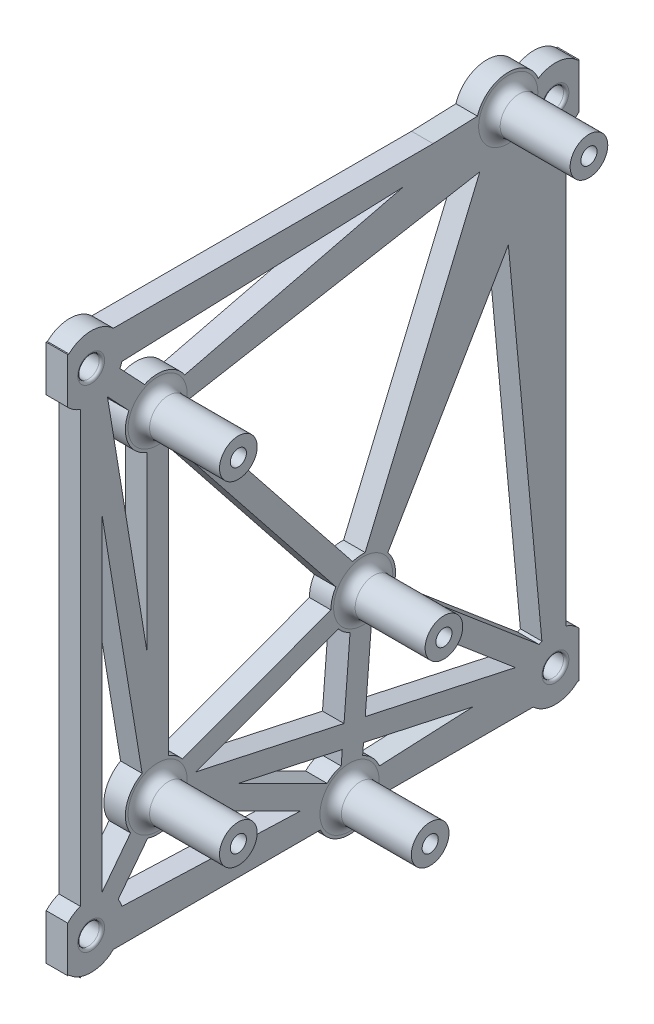
SolidWorks part; units mm, degrees
ref_plane "Front Plane" through (0, 0, 0) normal (0, 0, 1) x (1, 0, 0)
ref_plane "Top Plane" through (0, 0, 0) normal (0, 1, 0) x (1, 0, 0)
ref_plane "Right Plane" through (0, 0, 0) normal (1, 0, 0) x (0, 0, -1)
sketch "Sketch1" plane through (0, 0, 0) normal (1, 0, 0) x (0, 0, -1)
  line L1 (-43.15, -45.65) -> (43.15, -45.65)
  line L2 (-43.15, -45.65) -> (-43.15, 45.65)
  line L3 (-43.15, 45.65) -> (43.15, 45.65)
  line L4 (43.15, -45.65) -> (43.15, 45.65)
  line L5 (0, 45.65) -> (0, -45.65) construction
  line L6 (-43.15, 0) -> (43.15, 0) construction
  line L7 (-47.5, 55) -> (47.5, 55)
  line L8 (-47.5, 55) -> (-47.5, -55)
  line L9 (-47.5, -55) -> (47.5, -55)
  line L10 (47.5, 55) -> (47.5, -55)
  line L11 (0, -55) -> (0, 55) construction
  line L12 (-47.5, 0) -> (47.5, 0) construction
  circle A0 centre (-43.15, 45.65) radius 2
  circle A1 centre (43.15, 45.65) radius 2
  circle A2 centre (43.15, -45.65) radius 2
  circle A3 centre (-43.15, -45.65) radius 2
  point P0 (0, 0)
  point P4 (0, 0)
  dimension "D5" = 4
  dimension "D1" = 86.3
  dimension "D2" = 91.3
  dimension "D3" = 95
  dimension "D4" = 110
extrude "Boss-Extrude1" add sketch "Sketch1" along normal blind 4 contours L10 L7 L8 L9 L1 A3 L2 A0 L3 A1 L4 A2 | L2 A3 L1 A2 L4 A1 L3 A0
sketch "Sketch2" plane through (4, 0, 0) normal (1, 0, 0) x (0, 0, -1)
  line L0 (1978.982, -1041.5935) -> (1978.982, -941.5935) construction
  line L1 (-33.3282, 50.0149) -> (36.9218, 50.0149)
  line L2 (-33.3282, 50.0149) -> (-33.3282, -49.9851)
  line L3 (-33.3282, -49.9851) -> (36.9218, -49.9851)
  line L4 (36.9218, 50.0149) -> (36.9218, -49.9851)
  line L5 (1.7968, -49.9851) -> (1.7968, 50.0149) construction
  line L6 (-33.3282, 0.0149) -> (36.9218, 0.0149) construction
  circle A0 centre (34.3818, 48.5149) radius 1.5
  circle A1 centre (4.8718, -47.4451) radius 1.5
  circle A2 centre (-30.7882, 32.5649) radius 1.5
  circle A3 centre (-30.7882, -29.5851) radius 1.5
  circle A4 centre (7.4218, -15.4851) radius 1.5
  circle A5 centre (4.8718, -47.4451) radius 3.5
  circle A6 centre (-30.7882, -29.5851) radius 3.5
  circle A7 centre (7.4218, -15.4851) radius 3.5
  circle A8 centre (-30.7882, 32.5649) radius 3.5
  circle A9 centre (34.3818, 48.5149) radius 3.5
  point P0 (1.7968, 0.0149)
  dimension "D4" = 3
  dimension "D5" = 3
  dimension "D8" = 3
  dimension "D9" = 3
  dimension "D14" = 3
  dimension "D1" = 100
  dimension "D2" = 70.25
  dimension "D3" = 2.54
  dimension "D6" = 2.54
  dimension "D7" = 38.2
  dimension "D10" = 2.54
  dimension "D11" = 2.54
  dimension "D12" = 82.55
  dimension "D13" = 20.4
  dimension "D15" = 29.5
  dimension "D16" = 34.5
  dimension "D17" = 2
extrude "Boss-Extrude2" add sketch "Sketch2" along normal blind 15 contours L3 A5 A1 | L3 A5 | L2 A6 | L2 A6 A3 | A7 A4 | L2 A8 A2 | L2 A8 | L1 A9 L4 A0 | L4 A9 L1
sketch "Sketch3" plane through (4, 0, 0) normal (1, 0, 0) x (0, 0, -1)
  line L0 (-47.5, -50) -> (47.5, -50)
  line L1 (-47.5, 55) -> (-47.5, -55) construction
  line L2 (47.5, 55) -> (47.5, -55) construction
  line L3 (-47.5, 50) -> (47.5, 50)
  line L4 (-43.15, -45.65) -> (-30.7882, -29.5851)
  line L5 (-30.7882, -29.5851) -> (4.8718, -47.4451)
  line L6 (4.8718, -47.4451) -> (43.15, -45.65)
  line L7 (43.15, -45.65) -> (7.4218, -15.4851)
  line L8 (7.4218, -15.4851) -> (43.15, 45.65)
  line L9 (43.15, 45.65) -> (34.3818, 48.5149)
  line L10 (34.3818, 48.5149) -> (-43.15, 45.65)
  line L11 (-43.15, 45.65) -> (-30.7882, 32.5649)
  line L12 (-30.7882, 32.5649) -> (7.4218, -15.4851)
  line L13 (7.4218, -15.4851) -> (34.3818, 48.5149)
  line L14 (-30.7882, -29.5851) -> (-43.15, 45.65)
  line L15 (-30.7882, -29.5851) -> (-30.7882, 32.5649)
  line L16 (-43.15, -45.65) -> (-43.15, 45.65)
  line L17 (-30.7882, -29.5851) -> (7.4218, -15.4851)
  line L18 (-30.7882, -29.5851) -> (43.15, -45.65)
  line L19 (4.8718, -47.4451) -> (7.4218, -15.4851)
  line L20 (-30.7882, 32.5649) -> (34.3818, 48.5149)
  line L21 (-30.7882, 32.5649) -> (43.15, 45.65)
  line L22 (43.15, -45.65) -> (43.15, 45.65)
  line L23 (43.15, -45.65) -> (34.3818, 48.5149)
  line L24 (34.308, 50.5136) -> (-43.2239, 47.6486)
  line L25 (-32.3536, 31.3201) -> (5.8564, -16.7299)
  line L26 (-30.3127, 30.6223) -> (34.8573, 46.5723)
  line L27 (-30.4396, 30.5955) -> (43.4985, 43.6806)
  line L28 (-28.8146, -29.2608) -> (-41.1765, 45.9743)
  line L29 (-41.15, -39.7713) -> (-32.3732, -28.3654)
  line L30 (-41.15, -39.7713) -> (-41.15, 45.65)
  line L31 (-30.0958, -31.4614) -> (8.1142, -17.3614)
  line L32 (-28.7882, -29.5851) -> (-28.7882, 32.5649)
  line L33 (-31.2128, -31.5395) -> (42.7254, -47.6044)
  line L34 (-31.6838, -31.3733) -> (3.9762, -49.2333)
  line L35 (4.9655, -49.4429) -> (43.2437, -47.6478)
  line L36 (6.8655, -47.6041) -> (9.4155, -15.6441)
  line L37 (44.4402, -44.1218) -> (8.7121, -13.9569)
  line L38 (45.1414, -45.4646) -> (36.3732, 48.7004)
  line L39 (45.15, -45.65) -> (45.15, 45.65)
  line L40 (9.265, -16.2615) -> (36.225, 47.7385)
  line L41 (9.1486, -16.4942) -> (44.8767, 44.6409)
  line L42 (-44.6038, 44.2765) -> (-32.242, 31.1915)
  line L43 (34.4557, 46.5163) -> (-43.0761, 43.6514)
  line L44 (-29.2228, 33.8098) -> (8.9872, -14.2402)
  line L45 (-31.2636, 34.5076) -> (33.9064, 50.4576)
  line L46 (-31.1367, 34.5343) -> (42.8015, 47.6194)
  line L47 (-32.7617, -29.9093) -> (-45.1235, 45.3257)
  line L48 (-45.15, -51.5287) -> (-29.2031, -30.8047)
  line L49 (-45.15, -51.5287) -> (-45.15, 45.65)
  line L50 (-31.4806, -27.7087) -> (6.7294, -13.6087)
  line L51 (-32.7882, -29.5851) -> (-32.7882, 32.5649)
  line L52 (-30.3635, -27.6307) -> (43.5746, -43.6956)
  line L53 (-29.8925, -27.7968) -> (5.7675, -45.6568)
  line L54 (4.7781, -45.4473) -> (43.0563, -43.6522)
  line L55 (2.8782, -47.286) -> (5.4282, -15.326)
  line L56 (41.8598, -47.1782) -> (6.1316, -17.0132)
  line L57 (41.1586, -45.8354) -> (32.3904, 48.3295)
  line L58 (41.15, -45.65) -> (41.15, 45.65)
  line L59 (5.5787, -14.7086) -> (32.5387, 49.2914)
  line L60 (5.6951, -14.4759) -> (41.4233, 46.6591)
  line L61 (-41.6962, 47.0235) -> (-29.3343, 33.9384)
  line L62 (-43.15, -45.65) -> (4.8718, -47.4451)
  line L63 (-43.2247, -47.6486) -> (4.7971, -49.4437)
  line L64 (-43.0753, -43.6514) -> (4.9465, -45.4465)
  circle A0 centre (-43.15, -45.65) radius 2 construction
  circle A1 centre (4.8718, -47.4451) radius 6
  circle A2 centre (43.15, 45.65) radius 2 construction
  circle A3 centre (34.3818, 48.5149) radius 6
  circle A4 centre (-30.7882, 32.5649) radius 6
  circle A5 centre (-30.7882, -29.5851) radius 6
  circle A6 centre (7.4218, -15.4851) radius 6
  circle A7 centre (43.15, -45.65) radius 6
  circle A8 centre (-43.15, -45.65) radius 6
  circle A9 centre (-43.15, 45.65) radius 6
  circle A10 centre (43.15, 45.65) radius 6
  line M30 (47.5, -55) -> (47.5, 55)
  line M31 (47.5, 55) -> (-47.5, 55)
  line M32 (-47.5, 55) -> (-47.5, -55)
  line M33 (-47.5, -55) -> (47.5, -55)
  dimension "D3" = 12
  dimension "D4" = 12
  dimension "D5" = 12
  dimension "D6" = 12
  dimension "D7" = 12
  dimension "D8" = 12
  dimension "D9" = 12
  dimension "D10" = 12
  dimension "D11" = 12
  dimension "D1" = 4.35
  dimension "D2" = 4.35
  dimension "D12" = 2
  dimension "D13" = 2
  dimension "D14" = 2
  dimension "D15" = 2
extrude "Cut-Extrude1" cut sketch "Sketch3" against normal through all contours A8 L0 A7 A1 L48 L49 M32 M33 M30 | A10 L3 A9 L24 A3 M30 M31 M32 | A9 L61 A4 L45 L43 | A6 L59 L27 A4 L44 | A7 L57 L41 A6 L37 | A5 L47 L30 L29 | A8 L64 L34 A5 L48 | A6 L31 L52 L55 | A6 L36 L52 L56 | A6 L25 L32 A5 L50 | A4 L42 L28 L51 | A1 L54 L33 L36 | A1 L55 L33 L53 | A9 A8 L49 M32 | A10 L39 A7 M30
fillet "Fillet1" radius 2 5 edges at (4, -47.4451, -8.3718) (4, -15.4851, -10.9218) (4, -29.5851, 27.2882) (4, 32.5649, 27.2882) (4, 48.5149, -37.8818)
fillet "Fillet2" radius 0.5 4 edges at (4, 45.65, -45.15) (4, -45.65, -45.15) (4, -45.65, 41.15) (4, 45.65, 41.15)
